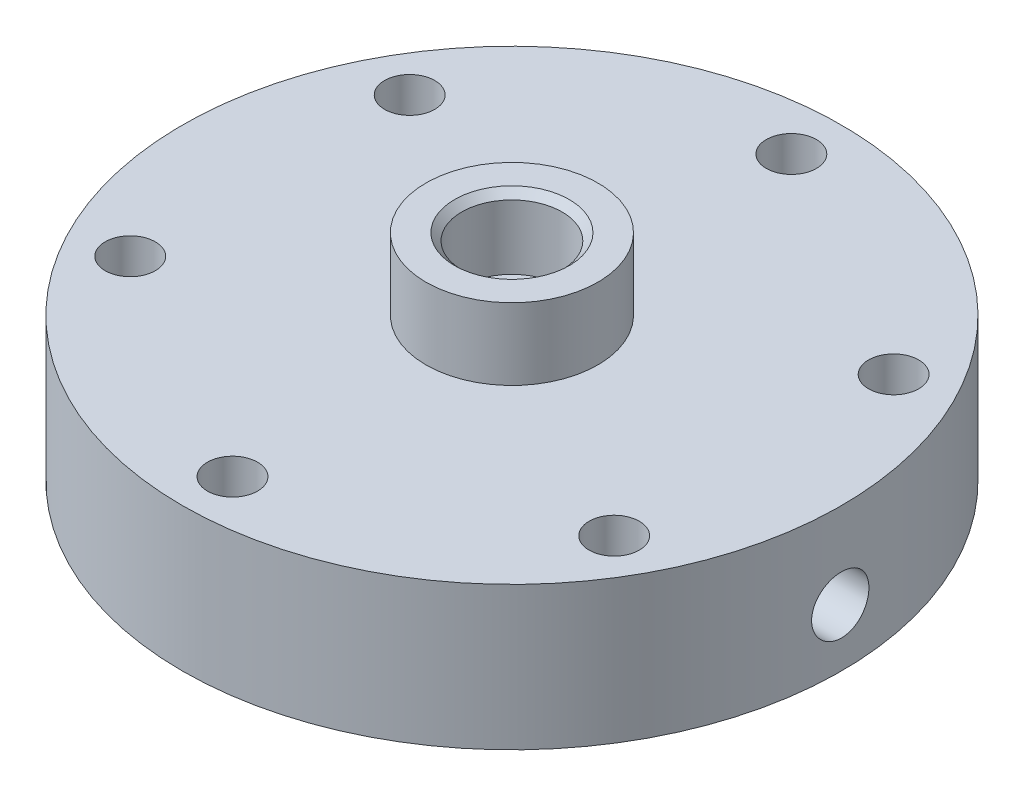
SolidWorks part; units mm, degrees
ref_plane "Front Plane" through (0, 0, 0) normal (0, 0, 1) x (1, 0, 0)
ref_plane "Top Plane" through (0, 0, 0) normal (0, 1, 0) x (1, 0, 0)
ref_plane "Right Plane" through (0, 0, 0) normal (1, 0, 0) x (0, 0, -1)
sketch "Sketch1" plane through (0, 0, 0) normal (0, 1, 0) x (1, 0, 0)
  circle A0 centre (0, 0) radius 46
  circle A1 centre (0, 0) radius 39 construction
  circle A2 centre (0, 39) radius 3.5
  circle A3 centre (33.775, 19.5) radius 3.5
  circle A4 centre (33.775, -19.5) radius 3.5
  circle A5 centre (0, -39) radius 3.5
  circle A6 centre (-33.775, -19.5) radius 3.5
  circle A7 centre (-33.775, 19.5) radius 3.5
  point P19 (0, 0)
  dimension "D1" = 92
  dimension "D2" = 78
  dimension "D3" = 7
  dimension "D4" = 6
extrude "Boss-Extrude1" add sketch "Sketch1" along normal blind 20
sketch "Sketch2" plane through (0, 20, 0) normal (0, 1, 0) x (1, 0, 0)
  circle A0 centre (0, 0) radius 12
  dimension "D1" = 24
extrude "Boss-Extrude2" add sketch "Sketch2" along normal blind 10
sketch "Sketch3" plane through (0, 0, 0) normal (0, -1, 0) x (1, 0, 0)
  circle A1 centre (0, 0) radius 33
  dimension "D1" = 66
extrude "Cut-Extrude1" cut sketch "Sketch3" against normal blind 14
sketch "Sketch4" plane through (0, 14, 0) normal (0, -1, 0) x (1, 0, 0)
  circle A0 centre (0, 0) radius 2.5
  dimension "D1" = 5
extrude "Cut-Extrude2" cut sketch "Sketch4" against normal blind 6
sketch "Sketch5" plane through (0, 30, 0) normal (0, 1, 0) x (1, 0, 0)
  circle A0 centre (0, 0) radius 7
  dimension "D1" = 14
extrude "Cut-Extrude3" cut sketch "Sketch5" against normal blind 10
cosmetic thread "Cosmetic Thread1" parameters "D1"=10, "D2"=16
chamfer "Chamfer2" distance 1 angle 45 1 edges at (0, 30, 7)
sketch "Sketch6" plane through (0, 0, 0) normal (1, 0, 0) x (0, 0, -1)
  circle A0 centre (0, 8) radius 4
  point P2 (0, 0)
  dimension "D1" = 8
  dimension "D2" = 8
extrude "Cut-Extrude4" cut sketch "Sketch6" along normal through all
